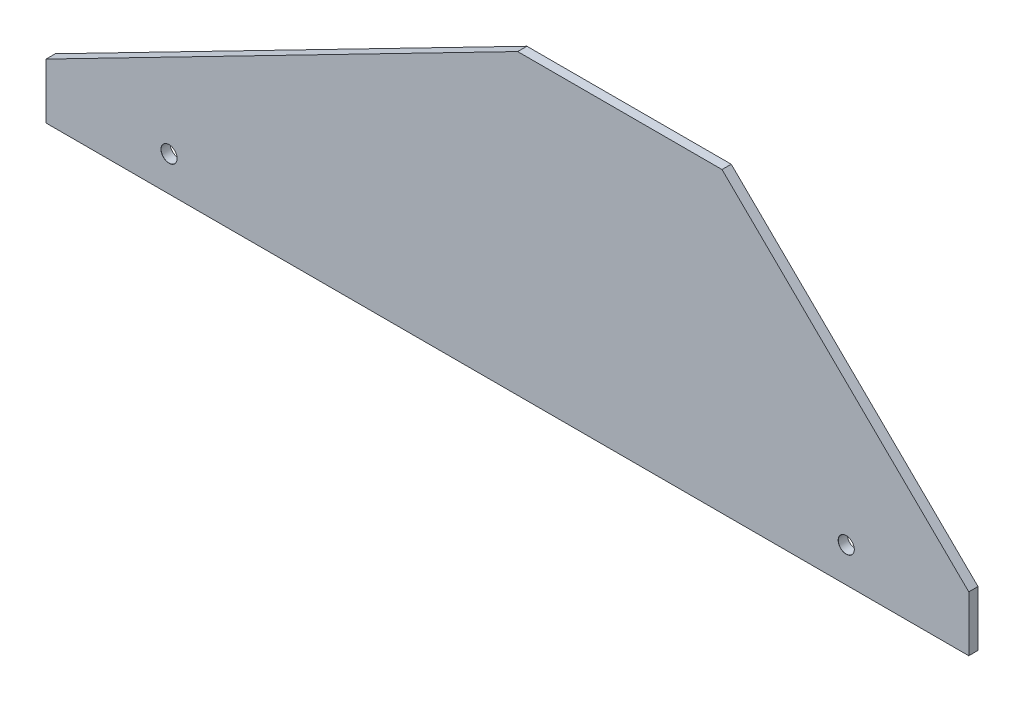
SolidWorks part; units mm, degrees
ref_plane "Ön Düzlem" through (0, 0, 0) normal (0, 0, 1) x (1, 0, 0)
ref_plane "Üst Düzlem" through (0, 0, 0) normal (0, 1, 0) x (1, 0, 0)
ref_plane "Sağ Düzlem" through (0, 0, 0) normal (1, 0, 0) x (0, 0, -1)
sketch "Çizim1" plane through (0, 0, 0) normal (0, 0, 1) x (1, 0, 0)
  line L0 (-150, 0) -> (150, 0)
  line L1 (-150, 0) -> (-150, 18)
  line L2 (-150, 18) -> (3.3427, 96.7885)
  line L3 (3.3427, 96.7885) -> (69.7684, 96.7885)
  line L4 (69.7684, 96.7885) -> (150, 18)
  line L5 (150, 18) -> (150, 0)
  line L6 (59.4261, 96.7885) -> (3.3427, 96.7885)
  point P4 (0, 0)
  dimension "D1" = 300
  dimension "D2" = 18
extrude "Yükseklik-Ekstrüzyon1" add sketch "Çizim1" along normal blind 3 contours L5 L4 L3 L2 L1 L0
sketch "Çizim2" plane through (0, 0, 3) normal (0, 0, 1) x (1, 0, 0)
  line L0 (-150, 18) -> (-110, 18) construction
  line L1 (-110, 18) -> (-110, 11.3) construction
  line L2 (150, 18) -> (110.16, 18) construction
  line L3 (110.16, 18) -> (110.16, 11.3) construction
  point P1 (-110, 18)
  point P5 (110.16, 18)
  point P12 (-110, 18)
  point P16 (110.16, 18)
  dimension "D1" = 40
  dimension "D2" = 6.7
  dimension "D3" = 39.84
  dimension "D4" = 6.7
sketch "Çizim9" plane through (0, 0, 3) normal (0, 0, 1) x (1, 0, 0)
  point P0 (-110, 11.3)
  point P3 (110.16, 11.3)
hole_wizard "M5 Helisarmal için Zıvana matkabı3" positions "Çizim9" profile "Çizim8" hole size "M5x0.8" standard "DIN"
sketch "Çizim8" plane through (-110, 11.3, 3) normal (1, 0, 0) x (0, -1, 0)
  line L0 (0, 0) -> (0, 19.5622)
  line L1 (0, 19.5622) -> (2.6, 18)
  line L2 (2.6, 18) -> (2.6, 0.025)
  line L3 (2.6, 0.025) -> (2.625, 0)
  line L5 (2.625, 0) -> (0, 0)
  line L6 (-2.6, 0.025) -> (-2.625, 0) construction
  line L10 (0, 19.5622) -> (-2.6, 18) construction
  line L11 (0, -6.35) -> (0, 107.95) construction
  dimension "Hole Dia." = 5.2
  dimension "Hole Depth" = 18
  dimension "Near C'Sink Dia." = 5.25
  dimension "Near C'Sink Angle" = 90
  dimension "Drill Angle" = 118
sketch "Çizim6" plane through (0, 0, 3) normal (0, 0, 1) x (1, 0, 0)
  point P0 (-110, 11.3)
  point P3 (110.16, 11.3)
hole_wizard "M5 Helisarmal için Zıvana matkabı2" positions "Çizim6" profile "Çizim5" hole size "M5x0.8" standard "DIN"
sketch "Çizim5" plane through (-110, 11.3, 3) normal (1, 0, 0) x (0, -1, 0)
  line L0 (0, 0) -> (0, 19.5622)
  line L1 (0, 19.5622) -> (2.6, 18)
  line L2 (2.6, 18) -> (2.6, 0.025)
  line L3 (2.6, 0.025) -> (2.625, 0)
  line L5 (2.625, 0) -> (0, 0)
  line L6 (-2.6, 0.025) -> (-2.625, 0) construction
  line L10 (0, 19.5622) -> (-2.6, 18) construction
  line L11 (0, -6.35) -> (0, 107.95) construction
  dimension "Hole Dia." = 5.2
  dimension "Hole Depth" = 18
  dimension "Near C'Sink Dia." = 5.25
  dimension "Near C'Sink Angle" = 90
  dimension "Drill Angle" = 118
